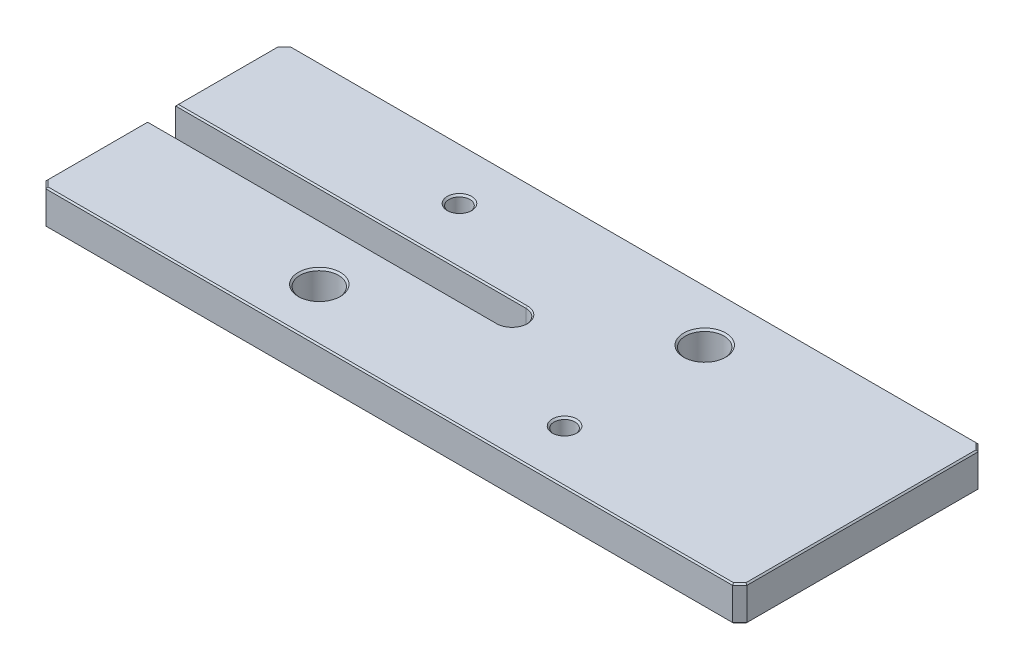
SolidWorks part; units mm, degrees
material "Plain Carbon Steel"
ref_plane "Front Plane" through (0, 0, 0) normal (0, 0, 1) x (1, 0, 0)
ref_plane "Top Plane" through (0, 0, 0) normal (0, 1, 0) x (1, 0, 0)
ref_plane "Right Plane" through (0, 0, 0) normal (1, 0, 0) x (0, 0, -1)
sketch "Sketch2" plane through (0, 0, 0) normal (0, 1, 0) x (1, 0, 0)
  line L0 (-50, 2) -> (0, 2)
  line L1 (0, -2) -> (-50, -2)
  line L2 (-50, 2) -> (-50, 17.5)
  line L3 (-50, 17.5) -> (50, 17.5)
  line L4 (50, 17.5) -> (50, -17.5)
  line L5 (50, -17.5) -> (-50, -17.5)
  line L6 (-50, -17.5) -> (-50, -2)
  line L8 (17.5, -10) -> (-17.5, -10) construction
  line L9 (17.5, -10) -> (17.5, 10) construction
  line L10 (17.5, 10) -> (-17.5, 10) construction
  line L11 (-17.5, -10) -> (-17.5, 10) construction
  line L12 (17.5, -10) -> (-17.5, 10) construction
  line L13 (17.5, 10) -> (-17.5, -10) construction
  arc A0 (0, -2) -> (0, 2) centre (0, 0) ccw
  circle A1 centre (0, 0) radius 8.5 construction
  circle A2 centre (0, 0) radius 10.5 construction
  point P10 (0, 17.5)
  dimension "D2" = 17
  dimension "D1" = 4
  dimension "D4" = 20
  dimension "D5" = 35
  dimension "D6" = 35
  dimension "D7" = 100
  dimension "D3" = 2
extrude "Boss-Extrude1" add sketch "Sketch2" along normal blind 5
hole_wizard "Ø3.0mm Dowel Hole1" positions "Sketch3" profile "Sketch4" hole size "Ø3.0" standard "ANSI Metric" end condition through all
sketch "Sketch3" plane through (0, 5, 0) normal (0, 1, 0) x (1, 0, 0)
  point P0 (-17.5, 10)
  point P3 (17.5, -10)
sketch "Sketch4" plane through (-17.5, 5, -10) normal (1, 0, 0) x (0, 0, 1)
  line L0 (0, 0) -> (0, 5)
  line L1 (0, 5) -> (1.75, 5)
  line L2 (1.5, 4.75) -> (1.5, 0.25)
  line L3 (1.5, 0.25) -> (1.75, 0)
  line L5 (1.75, 0) -> (0, 0)
  line L6 (-1.5, 0.25) -> (-1.75, 0) construction
  line L7 (1.75, 5) -> (1.5, 4.75)
  line L8 (-1.75, 5) -> (-1.5, 4.75) construction
  line L11 (0, -6.35) -> (0, 107.95) construction
  dimension "Thru Hole Dia." = 3
  dimension "Thru Hole Depth" = 5
  dimension "Near C'Sink Dia." = 3.5
  dimension "Near C'Sink Angle" = 90
  dimension "Far C'Sink Dia." = 3.5
  dimension "Far C'Sink Angle" = 90
hole_wizard "M5 Clearance Hole1" positions "Sketch5" profile "Sketch6" hole size "M5" standard "ANSI Metric" end condition through all
sketch "Sketch5" plane through (0, 5, 0) normal (0, 1, 0) x (1, 0, 0)
  point P0 (-17.5, -10)
  point P3 (17.5, 10)
sketch "Sketch6" plane through (-17.5, 5, 10) normal (1, 0, 0) x (0, 0, 1)
  line L0 (0, 0) -> (0, 5)
  line L1 (0, 5) -> (3, 5)
  line L2 (2.75, 4.75) -> (2.75, 0.25)
  line L3 (2.75, 0.25) -> (3, 0)
  line L5 (3, 0) -> (0, 0)
  line L6 (-2.75, 0.25) -> (-3, 0) construction
  line L7 (3, 5) -> (2.75, 4.75)
  line L8 (-3, 5) -> (-2.75, 4.75) construction
  line L11 (0, -6.35) -> (0, 107.95) construction
  dimension "Thru Hole Dia." = 5.5
  dimension "Thru Hole Depth" = 5
  dimension "Near C'Sink Dia." = 6
  dimension "Near C'Sink Angle" = 90
  dimension "Far C'Sink Dia." = 6
  dimension "Far C'Sink Angle" = 90
chamfer "Chamfer1" distance 1 4 edges at (50, 2.5, -17.5) (50, 2.5, 17.5) (-50, 2.5, 17.5) (-50, 2.5, -17.5)
chamfer "Chamfer2" distance 0.2 24 edges at (-49.5, 0, -17) (-50, 0, -9.25) (-25, 0, -2) (2, 0, 0) (-25, 0, 2) (-50, 0, 9.25) (-49.5, 0, 17) (0, 0, 17.5) (49.5, 0, 17) (50, 0, 0) (49.5, 0, -17) (0, 0, -17.5) (49.5, 5, 17) (0, 5, 17.5) (-49.5, 5, 17) (-50, 5, 9.25) (-25, 5, 2) (2, 5, 0) (-25, 5, -2) (-50, 5, -9.25) (-49.5, 5, -17) (0, 5, -17.5) (49.5, 5, -17) (50, 5, 0)
